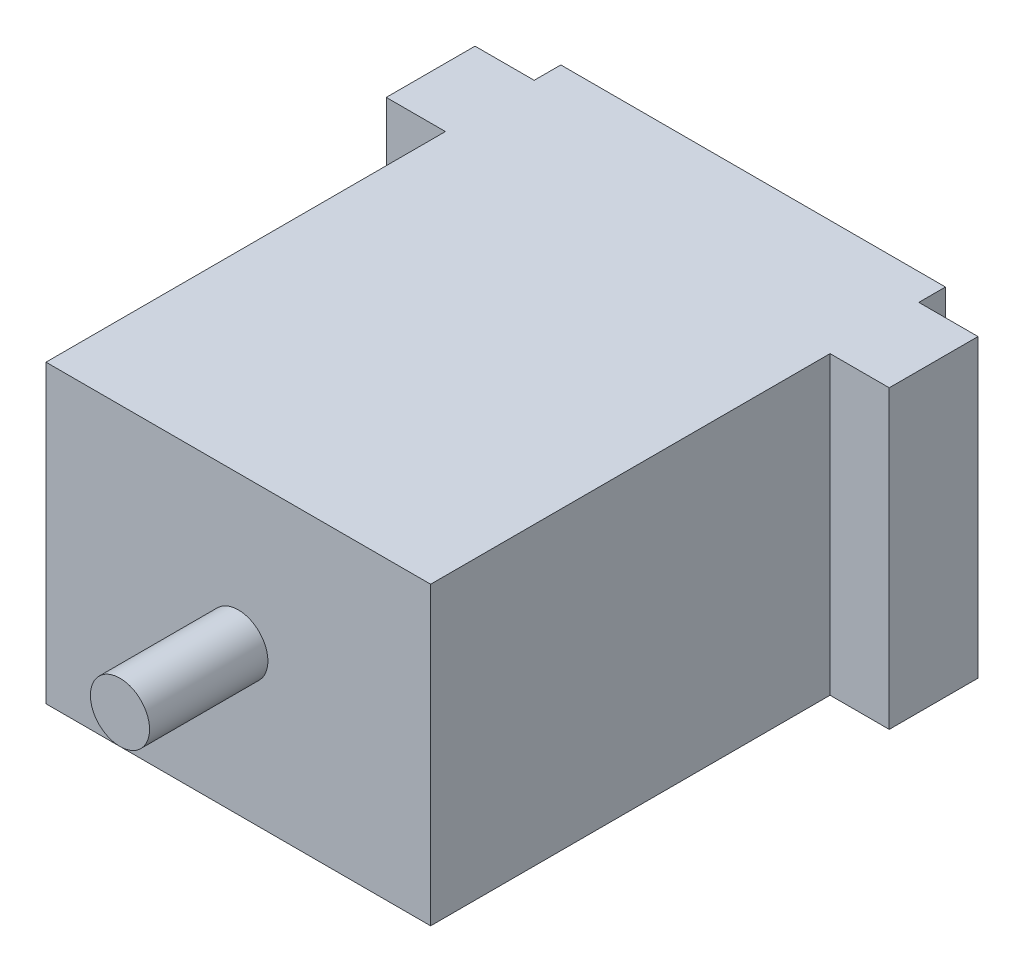
SolidWorks part; units mm, degrees
ref_plane "Front Plane" through (0, 0, 0) normal (0, 0, 1) x (1, 0, 0)
ref_plane "Top Plane" through (0, 0, 0) normal (0, 1, 0) x (1, 0, 0)
ref_plane "Right Plane" through (0, 0, 0) normal (1, 0, 0) x (0, 0, -1)
sketch "Sketch1" plane through (0, 0, 0) normal (0, 0, 1) x (1, 0, 0)
  line L1 (-32.5, 25) -> (32.5, 25)
  line L2 (-32.5, 25) -> (-32.5, -25)
  line L3 (-32.5, -25) -> (32.5, -25)
  line L4 (32.5, 25) -> (32.5, -25)
  line L5 (-32.5, 25) -> (32.5, -25) construction
  line L6 (-32.5, -25) -> (32.5, 25) construction
  point P0 (0, 0)
  dimension "D1" = 50
  dimension "D2" = 65
extrude "Boss-Extrude1" add sketch "Sketch1" along normal blind 150
sketch "Sketch2" plane through (32.5, 0, 0) normal (1, 0, 0) x (0, 0, -1)
  line L0 (-150, -25) -> (0, -25) construction
  line L1 (-82.5, 25) -> (-67.5, 25)
  line L2 (-82.5, 25) -> (-82.5, -25)
  line L3 (-82.5, -25) -> (-67.5, -25)
  line L4 (-67.5, 25) -> (-67.5, -25)
  line L5 (-82.5, 25) -> (-67.5, -25) construction
  line L6 (-82.5, -25) -> (-67.5, 25) construction
  line L7 (-150, 25) -> (0, 25) construction
  point P0 (-75, 0)
  point P7 (-75, 25)
  point P10 (-75, 25)
  dimension "D1" = 15
extrude "Boss-Extrude2" add sketch "Sketch2" along normal blind 10
mirror "Mirror1" about plane through (0, 0, 0) normal (1, 0, 0) of "Boss-Extrude2"
sketch "Sketch3" plane through (0, 0, 150) normal (0, 0, 1) x (1, 0, 0)
  circle A0 centre (0, 0) radius 5
  dimension "D1" = 10
extrude "Boss-Extrude3" add sketch "Sketch3" along normal blind 20
sketch "Sketch4" plane through (0, 25, 0) normal (0, 1, 0) x (1, 0, 0)
  line L0 (32.5, -67.5) -> (32.5, 0) construction
  line L1 (-32.5, 0) -> (32.5, 0)
  line L2 (-32.5, 0) -> (-32.5, -63)
  line L3 (-32.5, -63) -> (32.5, -63)
  line L4 (32.5, 0) -> (32.5, -63)
  dimension "D1" = 63
extrude "Cut-Extrude1" cut sketch "Sketch4" against normal through all
